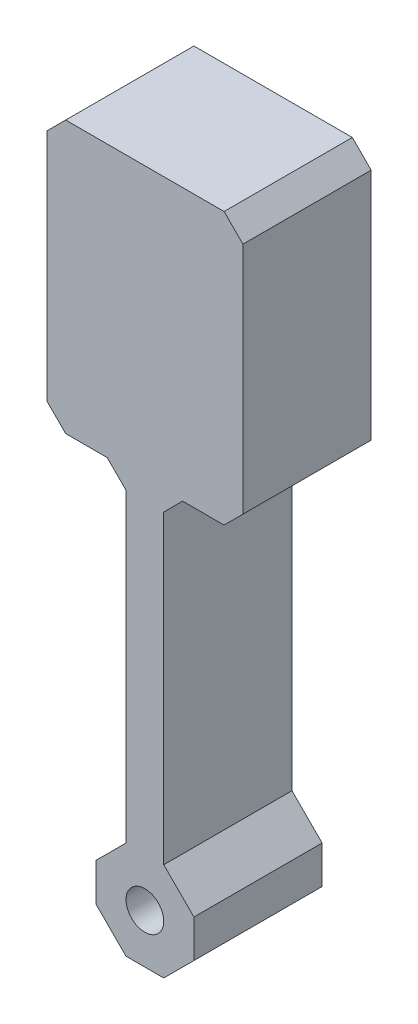
SolidWorks part; units mm, degrees
ref_plane "Front Plane" through (0, 0, 0) normal (0, 0, 1) x (1, 0, 0)
ref_plane "Top Plane" through (0, 0, 0) normal (0, 1, 0) x (1, 0, 0)
ref_plane "Right Plane" through (0, 0, 0) normal (1, 0, 0) x (0, 0, -1)
sketch "Sketch1" plane through (0, 0, 0) normal (0, 0, 1) x (1, 0, 0)
  line L0 (-13, -13) -> (-13, -23)
  line L1 (-13, -13) -> (13, -13)
  line L2 (-13, -13) -> (-13, 13)
  line L3 (-13, 13) -> (13, 13)
  line L4 (13, -13) -> (13, 13)
  line L5 (0, -72.5) -> (0, -5) construction
  line L6 (-13, -23) -> (0, -23) construction
  line L7 (-6.5, -70) -> (-6.5, -75)
  line L8 (13, -23) -> (13, -13)
  line L9 (0, -23) -> (13, -23) construction
  line L10 (-13, -5) -> (0, -5) construction
  line L11 (0, -5) -> (13, -5) construction
  line L12 (6.5, -70) -> (6.5, -75)
  line L13 (2.5, -79) -> (-2.5, -79)
  line L14 (-2.5, -66) -> (-2.5, -72.5) construction
  line L15 (-2.5, -72.5) -> (-2.5, -79) construction
  line L16 (-2.5, -79) -> (-6.5, -75)
  line L17 (-6.5, -70) -> (0, -70) construction
  line L18 (0, -70) -> (6.5, -70) construction
  line L19 (6.5, -75) -> (2.5, -79)
  line L20 (-6.5, -75) -> (0, -75) construction
  line L21 (0, -75) -> (6.5, -75) construction
  line L22 (-2.5, -66) -> (2.5, -66)
  line L23 (2.5, -66) -> (2.5, -72.5) construction
  line L24 (-6.5, -70) -> (-2.5, -66)
  line L25 (2.5, -72.5) -> (2.5, -79) construction
  line L26 (-2.5, -66) -> (-2.5, -23)
  line L27 (6.5, -70) -> (2.5, -66)
  line L28 (-2.5, -23) -> (2.5, -23)
  line L29 (2.5, -23) -> (2.5, -66)
  line L30 (-13, -23) -> (-2.5, -23)
  line L31 (2.5, -23) -> (13, -23)
  circle A0 centre (0, -72.5) radius 2.5
  point P0 (0, 0)
  dimension "D1" = 26
  dimension "D7" = 5
  dimension "D2" = 26
  dimension "D3" = 10
  dimension "D4" = 13
  dimension "D5" = 5
  dimension "D6" = 67.5
  dimension "D8" = 6.5
  dimension "D9" = 6.5
  dimension "D10" = 13
  dimension "D11" = 6.5
  dimension "D12" = 6.5
  dimension "D13" = 13
  dimension "D14" = 13
extrude "Boss-Extrude1" add sketch "Sketch1" along normal blind 17 contours L1 L4 L3 L2 | L28 L31 L8 L1 L0 L30 | L29 L28 L26 L22 | L12 L27 L22 L24 L7 L16 L13 L19 A0
chamfer "Chamfer1" distance 2.5 angle 45 6 edges at (-13, 13, 8.5) (13, 13, 8.5) (13, -23, 8.5) (2.5, -23, 8.5) (-2.5, -23, 8.5) (-13, -23, 8.5)
